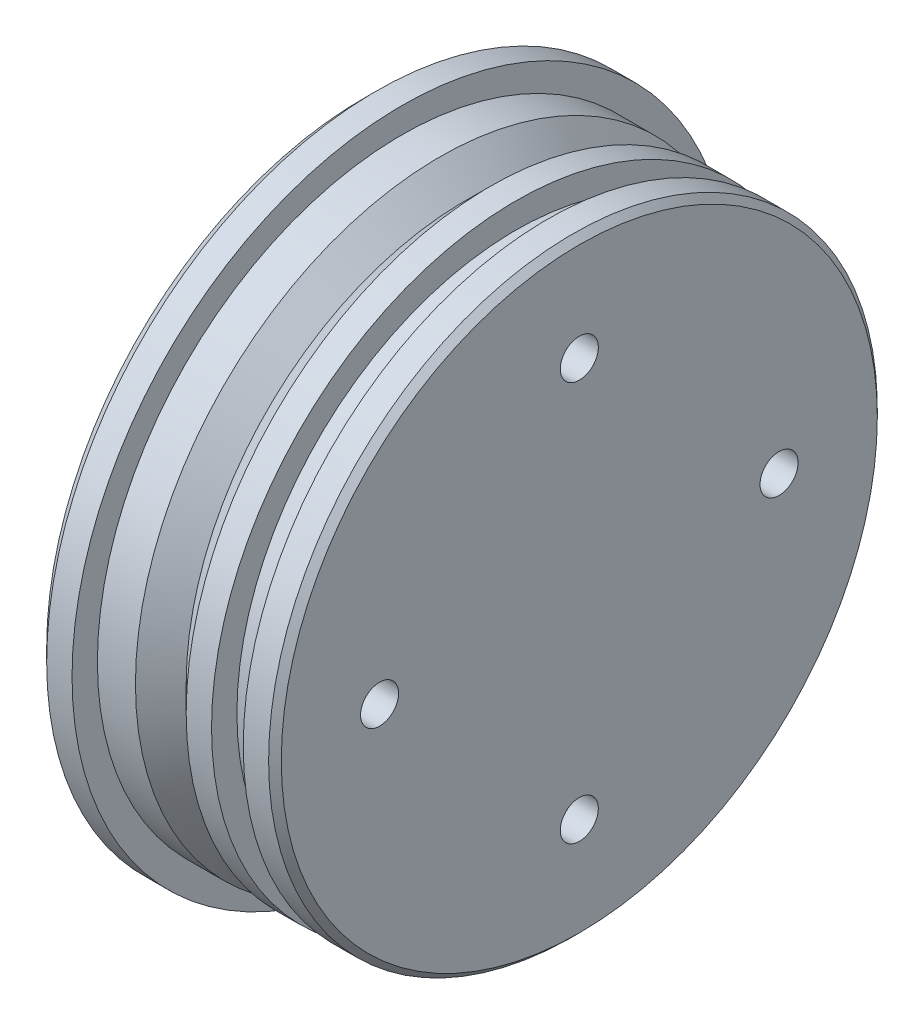
SolidWorks part; units mm, degrees
material "1060 Сплав"
ref_plane "Спереди" through (0, 0, 0) normal (0, 0, 1) x (1, 0, 0)
ref_plane "Сверху" through (0, 0, 0) normal (0, 1, 0) x (1, 0, 0)
ref_plane "Справа" through (0, 0, 0) normal (1, 0, 0) x (0, 0, -1)
sketch "Эскиз1" plane through (0, 0, 0) normal (0, 0, 1) x (1, 0, 0)
  line L0 (0, 0) -> (75.9362, 0) construction
  line L1 (-17, 0) -> (-17, 25)
  line L2 (-16, 26) -> (-14, 26)
  line L3 (-14, 26) -> (-14, 24)
  line L4 (-14, 24) -> (-11, 24)
  line L5 (-11, 24) -> (-9, 22)
  line L6 (-9, 22) -> (-7, 24)
  line L7 (-7, 24) -> (-5, 24)
  line L8 (-5, 24) -> (-5, 22)
  line L9 (-5, 22) -> (-2.5, 22)
  line L10 (-2.5, 22) -> (-2.5, 24)
  line L11 (-2.5, 24) -> (-0.5, 24)
  line L12 (0, 23.5) -> (0, 0)
  line L15 (-17, 25) -> (-16, 26)
  line L16 (-0.5, 24) -> (0, 23.5)
  line L18 (-17, 0) -> (0, 0)
  point P5 (-17, 26)
  point P16 (0, 24)
  dimension "D1" = 135
  dimension "D2" = 2
  dimension "D3" = 3
  dimension "D4" = 2.5
  dimension "D6" = 2
  dimension "D7" = 5
  dimension "D8" = 2
  dimension "D9" = 2.5
  dimension "D10" = 2
  dimension "D11" = 52
revolve "Повернуть1" add sketch "Эскиз1" angle 360 about L0
sketch "Эскиз2" plane through (0, 0, 0) normal (1, 0, 0) x (0, 0, -1)
  line L0 (0, 0) -> (-17.8433, 0) construction
  circle A0 centre (-15.75, 0) radius 1.5
  circle A1 centre (0, 15.75) radius 1.5
  circle A2 centre (15.75, 0) radius 1.5
  circle A3 centre (0, -15.75) radius 1.5
  point P11 (0, 0)
  dimension "D1" = 3
  dimension "D2" = 15.75
  dimension "D3" = 4
extrude "Вырез-Вытянуть1" cut sketch "Эскиз2" against normal blind 10 contours A1 | A2 | A0 | A3
